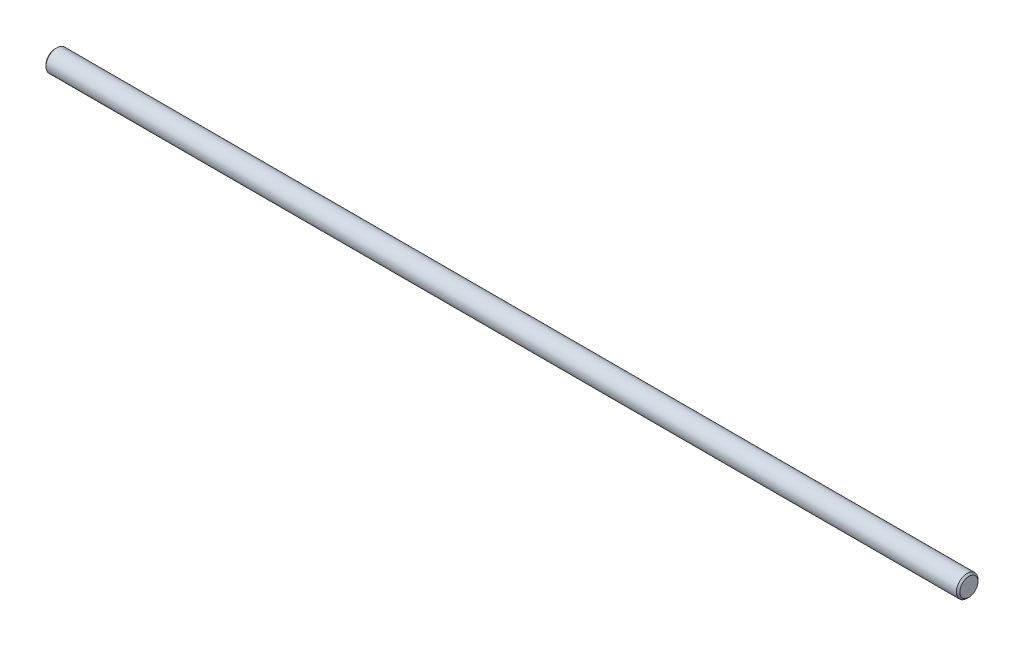
SolidWorks part; units mm, degrees
ref_plane "Front Plane" through (0, 0, 0) normal (0, 0, 1) x (1, 0, 0)
ref_plane "Top Plane" through (0, 0, 0) normal (0, 1, 0) x (1, 0, 0)
ref_plane "Right Plane" through (0, 0, 0) normal (1, 0, 0) x (0, 0, -1)
sketch "Sketch1" plane through (0, 0, 0) normal (1, 0, 0) x (0, 0, -1)
  circle A0 centre (0, 0) radius 7.5
  circle A1 centre (0, 0) radius 6.35
  dimension "D1" = 12.7
  dimension "D2" = 15
extrude "Boss-Extrude1" add sketch "Sketch1" along normal mid plane 536 contours A1
cosmetic thread "Cosmetic Thread1" parameters "D2"=10.072
cosmetic thread "Cosmetic Thread2" parameters "D2"=10.072
chamfer "Chamfer1" distance 1 angle 45 2 edges at (268, 0, -6.35) (-268, 0, -6.35)
